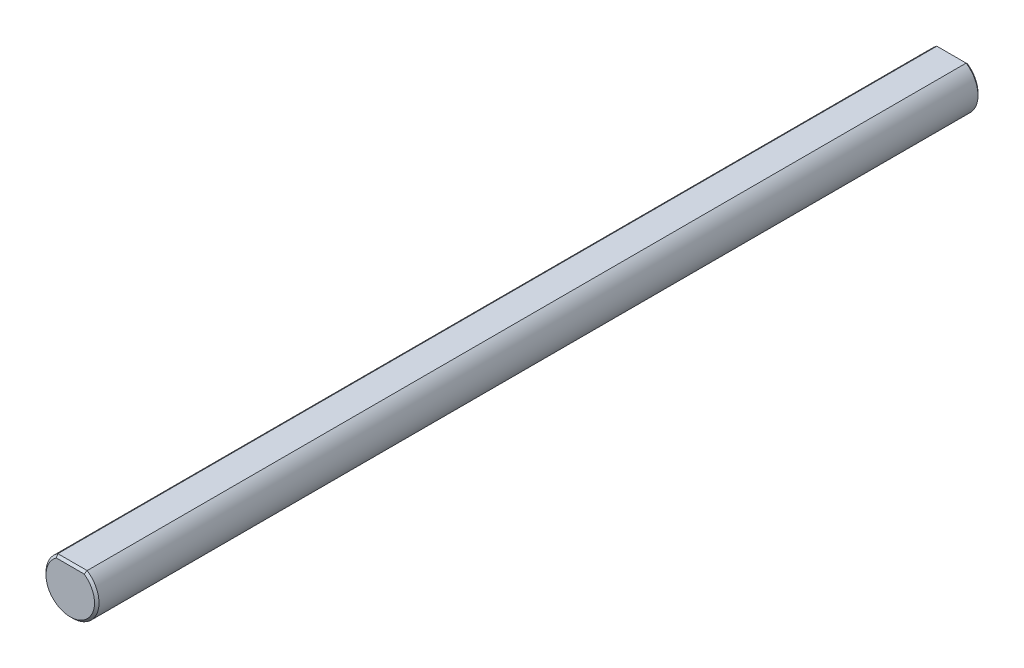
SolidWorks part; units mm, degrees
ref_plane "Front Plane" through (0, 0, 0) normal (0, 0, 1) x (1, 0, 0)
ref_plane "Top Plane" through (0, 0, 0) normal (0, 1, 0) x (1, 0, 0)
ref_plane "Right Plane" through (0, 0, 0) normal (1, 0, 0) x (0, 0, -1)
ref_plane "Plane4" through (0, 0, 100) normal (0, 0, 1) x (1, 0, 0)
sketch "Sketch1" plane through (0, 0, 100) normal (0, 0, 1) x (1, 0, 0)
  line L0 (1.6583, 2.5) -> (-1.6583, 2.5)
  arc A0 (-1.6583, 2.5) -> (1.6583, 2.5) centre (0, 0) ccw
extrude "Boss-Extrude1" add sketch "Sketch1" against normal blind 100
chamfer "Chamfer1" distance 0.254 angle 45 4 edges at (0, 2.5, 0) (0, -3, 0) (0, 2.5, 100) (0, -3, 100)
